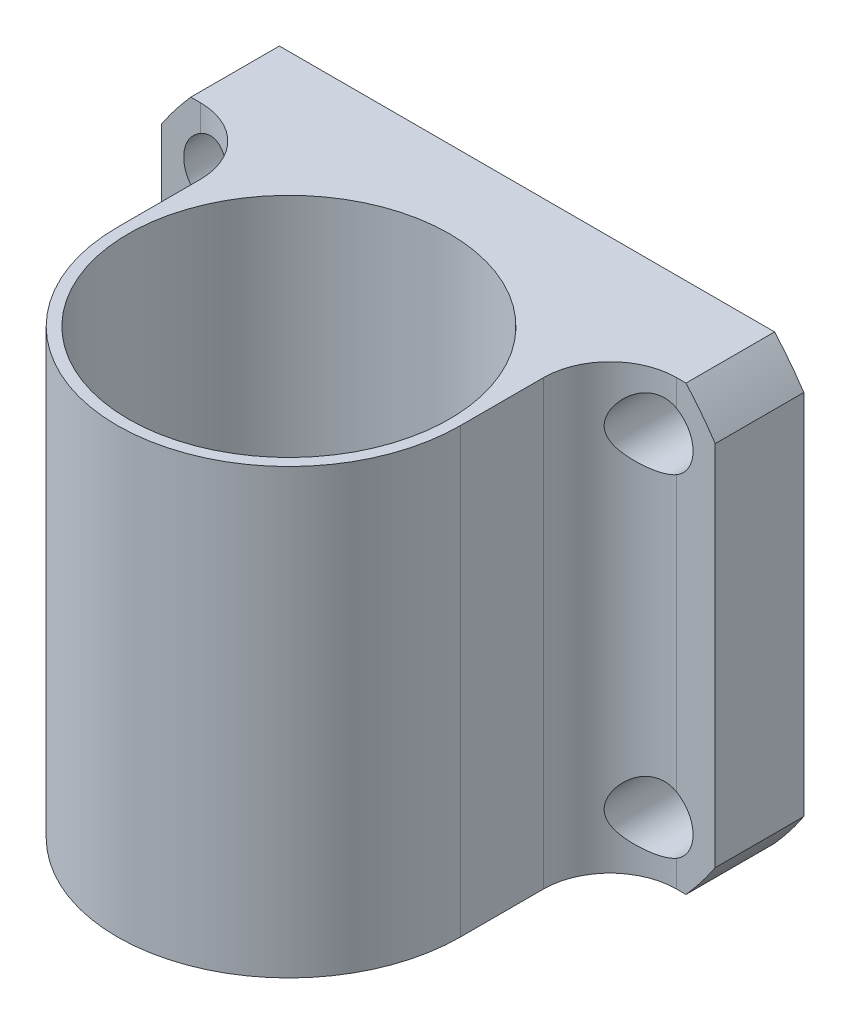
SolidWorks part; units mm, degrees
ref_plane "Спереди" through (0, 0, 0) normal (0, 0, 1) x (1, 0, 0)
ref_plane "Сверху" through (0, 0, 0) normal (0, 1, 0) x (1, 0, 0)
ref_plane "Справа" through (0, 0, 0) normal (1, 0, 0) x (0, 0, -1)
other "Configuration Table"
sketch "Sketch1" plane through (0, 0, 0) normal (0, 1, 0) x (1, 0, 0)
  line L0 (-25, 21.5) -> (-25, 13.5)
  line L2 (25, 21.5) -> (-25, 21.5)
  line L3 (0, 21) -> (0, -49.8117) construction
  line L6 (-15.5, 7.5) -> (-15.5, 0)
  line L14 (15.5, 7.5) -> (15.5, 0)
  line L15 (25, 21.5) -> (25, 13.5)
  line L22 (-21.5, 13.5) -> (-25, 13.5)
  line L23 (21.5, 13.5) -> (25, 13.5)
  circle A0 centre (0, 0) radius 14.5
  arc A3 (-15.5, 0) -> (15.5, 0) centre (0, 0) ccw
  arc A8 (-15.5, 7.5) -> (-21.5, 13.5) centre (-21.5, 7.5) ccw
  arc A9 (15.5, 7.5) -> (21.5, 13.5) centre (21.5, 7.5) cw
  point P6 (0, 0)
  point P7 (0, 0)
  point P17 (-20.413, 8.6092)
  point P18 (-21.8159, 7.1841)
  dimension "D1" = 29
  dimension "D2" = 50
  dimension "D4" = 1
  dimension "D6" = 6
  dimension "D3" = 7
  dimension "D5" = 8
extrude "Boss-Extrude1" add sketch "Sketch1" along normal mid plane 40
sketch "Sketch2" plane through (0, 0, -21.5) normal (0, 0, -1) x (-1, 0, 0)
  line L1 (-20, -15) -> (20, -15) construction
  line L2 (-20, -15) -> (-20, 15) construction
  line L3 (-20, 15) -> (20, 15) construction
  line L4 (20, -15) -> (20, 15) construction
  line L5 (-20, -15) -> (20, 15) construction
  line L6 (-20, 15) -> (20, -15) construction
  circle A0 centre (-20, 15) radius 3
  circle A1 centre (20, 15) radius 3
  circle A2 centre (20, -15) radius 3
  circle A3 centre (-20, -15) radius 3
  point P0 (0, 0)
  dimension "D3" = 6
  dimension "D1" = 40
  dimension "D2" = 30
extrude "Cut-Extrude1" cut sketch "Sketch2" against normal through all both and the other way through all
sketch "Sketch4" plane through (-25, 0, 0) normal (-1, 0, 0) x (0, 0, 1)
  line L0 (-36.3388, 0) -> (31.6463, 0) construction
  line L1 (-16.5, 20) -> (-16.5, 10)
  line L2 (-21.5, 20) -> (-13.5, 20) construction
  line L3 (-16.5, 10) -> (15.5, 10)
  line L4 (15.5, -20) -> (15.5, 20) construction
  line L5 (15.5, 10) -> (15.5, 20)
  line L6 (15.5, 20) -> (-16.5, 20)
  line L7 (-13.5, 20) -> (-13.5, 17.5981) construction
  line L8 (15.5, -20) -> (-16.5, -20)
  line L9 (15.5, -10) -> (15.5, -20)
  line L10 (-16.5, -10) -> (15.5, -10)
  line L11 (-16.5, -20) -> (-16.5, -10)
  dimension "D1" = 10
  dimension "D2" = 3
extrude "Cut-Extrude2" [suppressed] cut sketch "Sketch4" against normal through all both and the other way through all
sketch "Sketch5" plane through (0, 0, -21.5) normal (0, 0, -1) x (-1, 0, 0)
  circle A0 centre (0, 0) radius 30
  dimension "D1" = 60
extrude "Cut-Extrude-Thin1" cut sketch "Sketch5" against normal through all both thin
